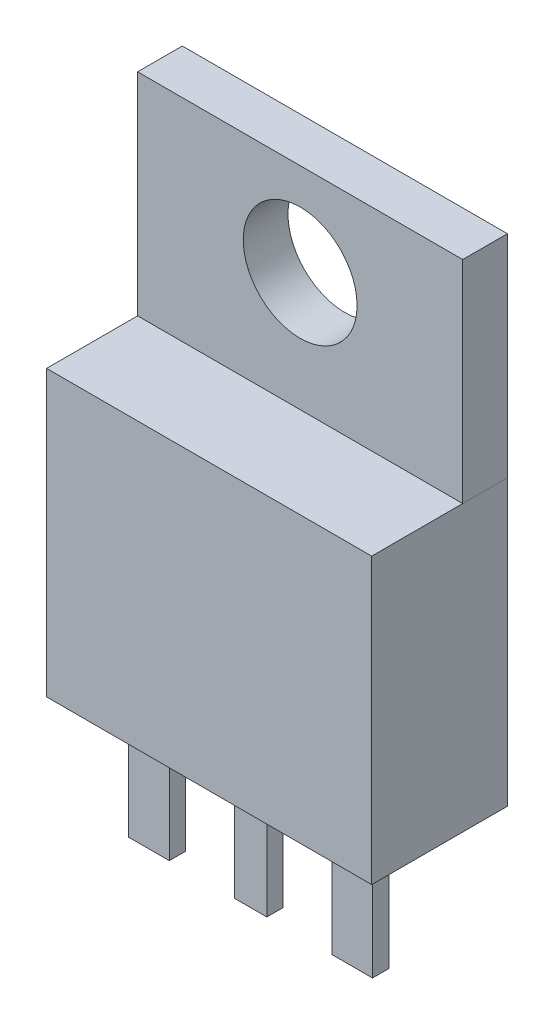
SolidWorks part; units mm, degrees
ref_plane "Front" through (0, 0, 0) normal (0, 0, 1) x (1, 0, 0)
ref_plane "Top" through (0, 0, 0) normal (0, 1, 0) x (1, 0, 0)
ref_plane "Right" through (0, 0, 0) normal (1, 0, 0) x (0, 0, -1)
sketch "Sketch2" plane through (0, 0, 0) normal (0, 0, 1) x (1, 0, 0)
  line L1 (-5.08, 3.302) -> (5.08, 3.302)
  line L2 (-5.08, 3.302) -> (-5.08, -3.302)
  line L3 (-5.08, -3.302) -> (5.08, -3.302)
  line L4 (5.08, 3.302) -> (5.08, -3.302)
  line L5 (-5.08, 3.302) -> (5.08, -3.302) construction
  line L6 (-5.08, -3.302) -> (5.08, 3.302) construction
  line L7 (-3.81, -3.302) -> (3.81, -3.302)
  line L8 (-3.81, -3.302) -> (-3.81, -9.144)
  line L9 (-3.81, -9.144) -> (3.81, -9.144)
  line L10 (3.81, -3.302) -> (3.81, -9.144)
  point P0 (0, 0)
  dimension "D1" = 6.604
  dimension "D2" = 10.16
  dimension "D3" = 5.842
  dimension "D4" = 7.62
  dimension "D5" = 1.27
extrude "Boss-Extrude1" add sketch "Sketch2" along normal blind 1.397 contours L4 L1 L2 L3 | L10 L3 L8 L9
sketch "Sketch3" plane through (0, 0, 1.397) normal (0, 0, 1) x (1, 0, 0)
  line L0 (5.08, 3.302) -> (5.08, -3.302) construction
  line L1 (-5.08, 3.302) -> (5.08, 3.302) construction
  circle A0 centre (0, 0.4064) radius 1.778
  dimension "D1" = 3.556
  dimension "D2" = 5.08
  dimension "D3" = 2.8956
extrude "Cut-Extrude1" cut sketch "Sketch3" against normal through all
sketch "Sketch4" plane through (0, 0, 0) normal (0, 0, 1) x (1, 0, 0)
  line L1 (-5.08, -3.302) -> (5.08, -3.302)
  line L2 (-5.08, -3.302) -> (-5.08, -12.192)
  line L3 (-5.08, -12.192) -> (5.08, -12.192)
  line L4 (5.08, -3.302) -> (5.08, -12.192)
  line L5 (-5.08, -3.302) -> (5.08, -12.192) construction
  line L6 (-5.08, -12.192) -> (5.08, -3.302) construction
  line L7 (3.81, -3.302) -> (5.08, -3.302) construction
  line L8 (3.81, -3.302) -> (3.81, -9.144) construction
  point P0 (0, -7.747)
  dimension "D1" = 10.16
  dimension "D2" = 8.89
  dimension "D3" = 1.27
extrude "Boss-Extrude2" add sketch "Sketch4" along normal blind 4.2418 separate body
sketch "Sketch7" plane through (0, 0, 0) normal (0, 0, -1) x (-1, 0, 0)
  line L0 (-5.08, -3.302) -> (5.08, -3.302) construction
  line L1 (-3.81, -3.302) -> (3.81, -3.302)
  line L2 (-3.81, -3.302) -> (-3.81, -9.144)
  line L3 (-3.81, -9.144) -> (3.81, -9.144)
  line L4 (3.81, -3.302) -> (3.81, -9.144)
  line L5 (-5.08, -12.192) -> (-5.08, -3.302) construction
  dimension "D1" = 5.842
  dimension "D2" = 7.62
  dimension "D3" = 1.27
extrude "Cut-Extrude3" cut sketch "Sketch7" against normal blind 1.397
sketch "Sketch8" plane through (0, -12.192, 0) normal (0, -1, 0) x (1, 0, 0)
  line L0 (-5.08, 0) -> (5.08, 0) construction
  line L1 (-3.81, 2.9464) -> (-2.54, 2.9464)
  line L2 (-3.81, 2.9464) -> (-3.81, 2.4384)
  line L3 (-3.81, 2.4384) -> (-2.54, 2.4384)
  line L4 (-2.54, 2.9464) -> (-2.54, 2.4384)
  line L5 (-3.81, 2.9464) -> (-2.54, 2.4384) construction
  line L6 (-3.81, 2.4384) -> (-2.54, 2.9464) construction
  line L7 (2.54, 2.9464) -> (3.81, 2.9464)
  line L8 (2.54, 2.9464) -> (2.54, 2.4384)
  line L9 (2.54, 2.4384) -> (3.81, 2.4384)
  line L10 (3.81, 2.9464) -> (3.81, 2.4384)
  line L11 (2.54, 2.9464) -> (3.81, 2.4384) construction
  line L12 (2.54, 2.4384) -> (3.81, 2.9464) construction
  line L13 (-5.08, 4.2418) -> (-5.08, 0) construction
  line L14 (-0.508, 2.9464) -> (0.508, 2.9464)
  line L15 (-0.508, 2.9464) -> (-0.508, 2.4384)
  line L16 (-0.508, 2.4384) -> (0.508, 2.4384)
  line L17 (0.508, 2.9464) -> (0.508, 2.4384)
  line L18 (-0.508, 2.9464) -> (0.508, 2.4384) construction
  line L19 (-0.508, 2.4384) -> (0.508, 2.9464) construction
  line L20 (5.08, 4.2418) -> (5.08, 0) construction
  point P0 (-3.175, 2.6924)
  point P5 (3.175, 2.6924)
  point P12 (0, 2.6924)
  dimension "D1" = 2.4384
  dimension "D2" = 2.4384
  dimension "D3" = 0.508
  dimension "D4" = 0.508
  dimension "D5" = 0.508
  dimension "D6" = 1.27
  dimension "D7" = 1.27
  dimension "D8" = 1.016
  dimension "D9" = 1.27
  dimension "D10" = 1.27
  dimension "D11" = 2.54
extrude "Boss-Extrude3" add sketch "Sketch8" along normal blind 3.81 separate body
